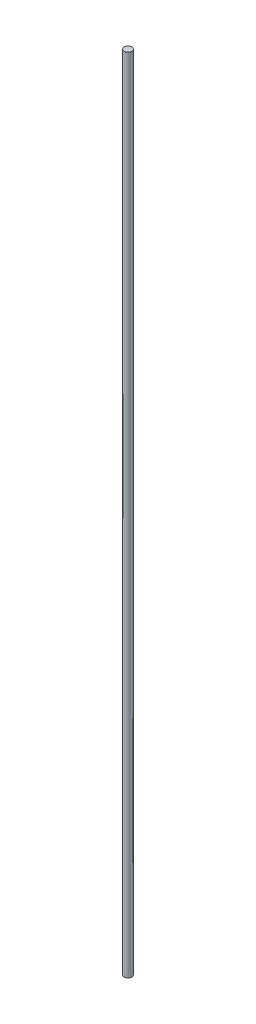
SolidWorks part; units mm, degrees
ref_plane "Front Plane" through (0, 0, 0) normal (0, 0, 1) x (1, 0, 0)
ref_plane "Top Plane" through (0, 0, 0) normal (0, 1, 0) x (1, 0, 0)
ref_plane "Right Plane" through (0, 0, 0) normal (1, 0, 0) x (0, 0, -1)
sketch "Sketch1" plane through (0, 0, 0) normal (0, 1, 0) x (1, 0, 0)
  circle A0 centre (0, 0) radius 4.7625
  dimension "D1" = 9.525
extrude "Boss-Extrude1" add sketch "Sketch1" along normal mid plane 1000
